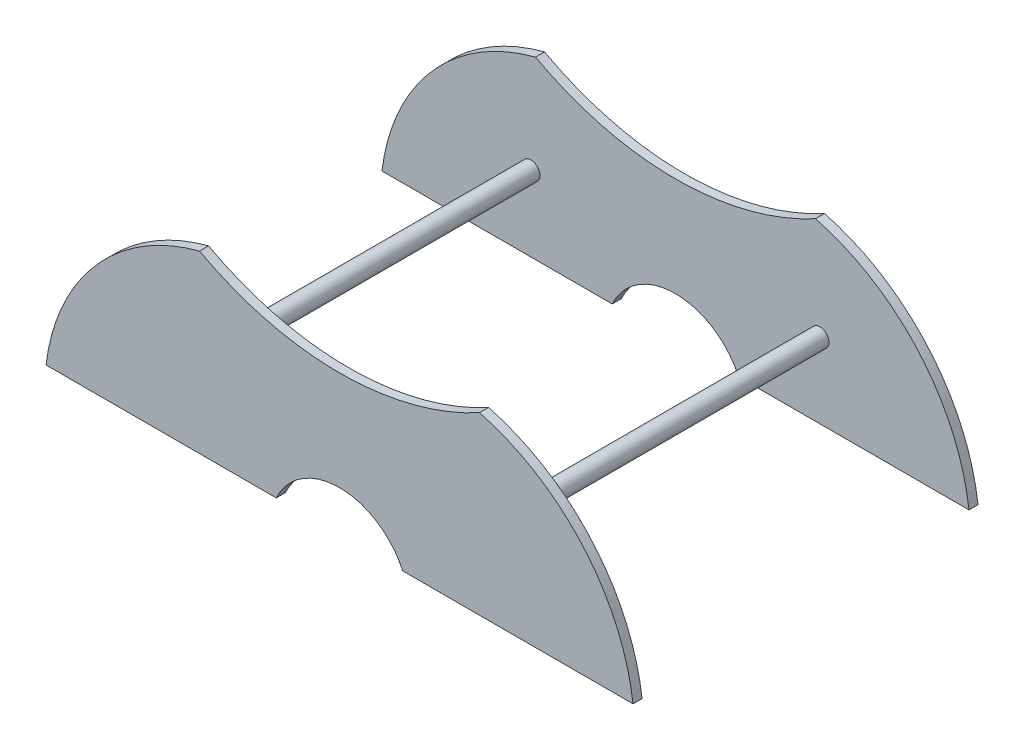
SolidWorks part; units mm, degrees
material "Glass"
ref_plane "Front Plane" through (0, 0, 0) normal (0, 0, 1) x (1, 0, 0)
ref_plane "Top Plane" through (0, 0, 0) normal (0, 1, 0) x (1, 0, 0)
ref_plane "Right Plane" through (0, 0, 0) normal (1, 0, 0) x (0, 0, -1)
sketch "Sketch1" plane through (0, 0, 0) normal (0, 0, 1) x (1, 0, 0)
  line L0 (-325, 0) -> (-70, 0)
  line L1 (70, 0) -> (325, 0)
  arc A0 (-70, 0) -> (70, 0) centre (0, -32.078) cw
  arc A1 (-325, 0) -> (-155, 194.234) centre (-96.7435, -28.2659) cw
  arc A2 (325, 0) -> (155, 194.234) centre (96.7435, -28.2659) ccw
  arc A6 (-155, 194.234) -> (155, 194.234) centre (0, 480.1462) ccw
  point P4 (0, 0)
  point P9 (0, 44.922)
  point P16 (0, 154.922)
  dimension "D4" = 170
  dimension "D5" = 170
  dimension "D3" = 77
  dimension "D6" = 110
  dimension "D7" = 230
  dimension "D1" = 140
  dimension "D2" = 650
extrude "Boss-Extrude1" add sketch "Sketch1" along normal blind 10
ref_plane "Plane1" through (0, 0, -362) normal (0, 0, 1) x (1, 0, 0)
sketch "Sketch2" plane through (0, 0, -362) normal (0, 0, 1) x (1, 0, 0)
  line L2 (70, 0) -> (325, 0)
  line L3 (-325, 0) -> (-70, 0)
  line L4 (70, 0) -> (325, 0)
  line L5 (-325, 0) -> (-70, 0)
  arc A4 (70, 0) -> (-70, 0) centre (0, -32.078) ccw
  arc A5 (325, 0) -> (155, 194.234) centre (96.7435, -28.2659) ccw
  arc A6 (-155, 194.234) -> (155, 194.234) centre (0, 480.1462) ccw
  arc A7 (-155, 194.234) -> (-325, 0) centre (-96.7435, -28.2659) ccw
  arc A8 (70, 0) -> (-70, 0) centre (0, -32.078) ccw
  arc A9 (325, 0) -> (155, 194.234) centre (96.7435, -28.2659) ccw
  arc A10 (-155, 194.234) -> (155, 194.234) centre (0, 480.1462) ccw
  arc A11 (-155, 194.234) -> (-325, 0) centre (-96.7435, -28.2659) ccw
  dimension "D1" = 0
extrude "Boss-Extrude2" add sketch "Sketch2" against normal blind 10 separate body
sketch "Sketch3" plane through (0, 0, 10) normal (0, 0, 1) x (1, 0, 0)
  circle A0 centre (-160, 83.101) radius 10
  circle A1 centre (0, 400) radius 345 construction
  circle A2 centre (160, 83.101) radius 10
  dimension "D2" = 20
  dimension "D3" = 160
  dimension "D1" = 160
extrude "Boss-Extrude3" add sketch "Sketch3" against normal up to surface (382 mm away) up to face at (0, 74.3783, -372)
